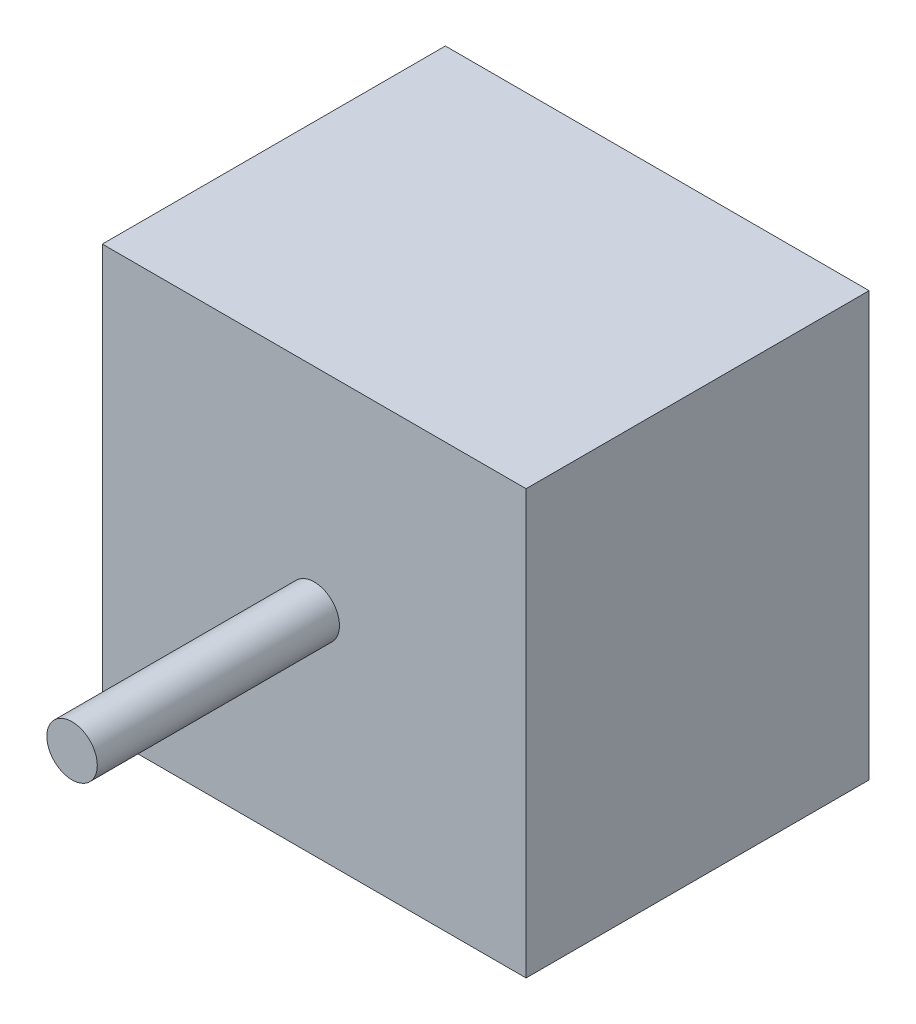
SolidWorks part; units mm, degrees
ref_plane "Plan de face" through (0, 0, 0) normal (0, 0, 1) x (1, 0, 0)
ref_plane "Plan de dessus" through (0, 0, 0) normal (0, 1, 0) x (1, 0, 0)
ref_plane "Plan de droite" through (0, 0, 0) normal (1, 0, 0) x (0, 0, -1)
sketch "Esquisse1" plane through (0, 0, 0) normal (0, 0, 1) x (1, 0, 0)
  line L1 (-21, 21) -> (21, 21)
  line L2 (-21, 21) -> (-21, -21)
  line L3 (-21, -21) -> (21, -21)
  line L4 (21, 21) -> (21, -21)
  line L5 (-21, 21) -> (21, -21) construction
  line L6 (-21, -21) -> (21, 21) construction
  point P0 (0, 0)
  dimension "D1" = 42
  dimension "D2" = 42
extrude "Boss.-Extru.1" add sketch "Esquisse1" along normal blind 34
sketch "Esquisse2" plane through (0, 0, 34) normal (0, 0, 1) x (1, 0, 0)
  circle A2 centre (0, 0) radius 2.5
  point P3 (0, 0)
extrude "Boss.-Extru.2" add sketch "Esquisse2" along normal blind 24
